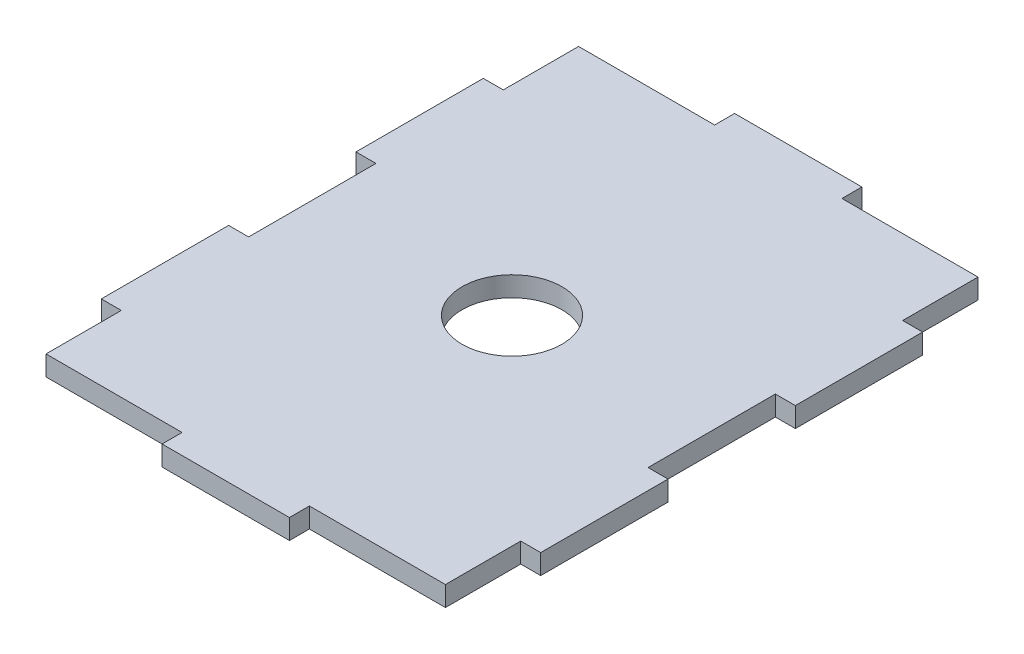
SolidWorks part; units mm, degrees
ref_plane "Front Plane" through (0, 0, 0) normal (0, 0, 1) x (1, 0, 0)
ref_plane "Top Plane" through (0, 0, 0) normal (0, 1, 0) x (1, 0, 0)
ref_plane "Right Plane" through (0, 0, 0) normal (1, 0, 0) x (0, 0, -1)
sketch "Sketch1" plane through (0, 0, 0) normal (0, 1, 0) x (1, 0, 0)
  line L0 (-13.8856, -10.7732) -> (-13.8856, -22.0857)
  line L1 (-13.8856, -22.0857) -> (-16.8856, -22.0857)
  line L2 (-16.8856, -22.0857) -> (-16.8856, -41.2107)
  line L3 (-16.8856, -41.2107) -> (-13.8856, -41.2107)
  line L4 (-13.8856, -41.2107) -> (-13.8856, -60.3357)
  line L5 (-13.8856, -60.3357) -> (-16.8856, -60.3357)
  line L6 (-16.8856, -60.3357) -> (-16.8856, -79.4607)
  line L7 (-16.8856, -79.4607) -> (-13.8856, -79.4607)
  line L8 (-13.8856, -79.4607) -> (-13.8856, -90.7732)
  line L9 (-13.8856, -90.7732) -> (6.5519, -90.7732)
  line L10 (6.5519, -90.7732) -> (6.5519, -93.7732)
  line L11 (6.5519, -93.7732) -> (25.6769, -93.7732)
  line L12 (25.6769, -93.7732) -> (25.6769, -90.7732)
  line L13 (25.6769, -90.7732) -> (44.8019, -90.7732)
  line L14 (44.8019, -90.7732) -> (46.1144, -90.7732)
  line L15 (46.1144, -90.7732) -> (46.1144, -79.4607)
  line L16 (46.1144, -79.4607) -> (49.1144, -79.4607)
  line L17 (49.1144, -79.4607) -> (49.1144, -60.3357)
  line L18 (49.1144, -60.3357) -> (46.1144, -60.3357)
  line L19 (46.1144, -60.3357) -> (46.1144, -41.2107)
  line L20 (46.1144, -41.2107) -> (49.1144, -41.2107)
  line L21 (49.1144, -41.2107) -> (49.1144, -22.0857)
  line L22 (49.1144, -22.0857) -> (46.1144, -22.0857)
  line L23 (46.1144, -22.0857) -> (46.1144, -10.7732)
  line L24 (46.1144, -10.7732) -> (25.6769, -10.7732)
  line L25 (25.6769, -10.7732) -> (25.6769, -7.7732)
  line L26 (25.6769, -7.7732) -> (6.5519, -7.7732)
  line L27 (6.5519, -7.7732) -> (6.5519, -10.7732)
  line L28 (6.5519, -10.7732) -> (-12.5731, -10.7732)
  line L29 (-12.5731, -10.7732) -> (-13.8856, -10.7732)
  line L30 (-16.8856, -7.7732) -> (49.1144, -93.7732) construction
  line L31 (-16.8856, -7.7732) -> (49.1144, -7.7732) construction
  line L32 (-16.8856, -7.7732) -> (-16.8856, -93.7732) construction
  line L33 (-16.8856, -93.7732) -> (49.1144, -93.7732) construction
  line L34 (49.1144, -7.7732) -> (49.1144, -93.7732) construction
  circle A0 centre (16.1144, -50.7732) radius 7.5
  dimension "D1" = 15
extrude "Boss-Extrude1" add sketch "Sketch1" along normal blind 3
